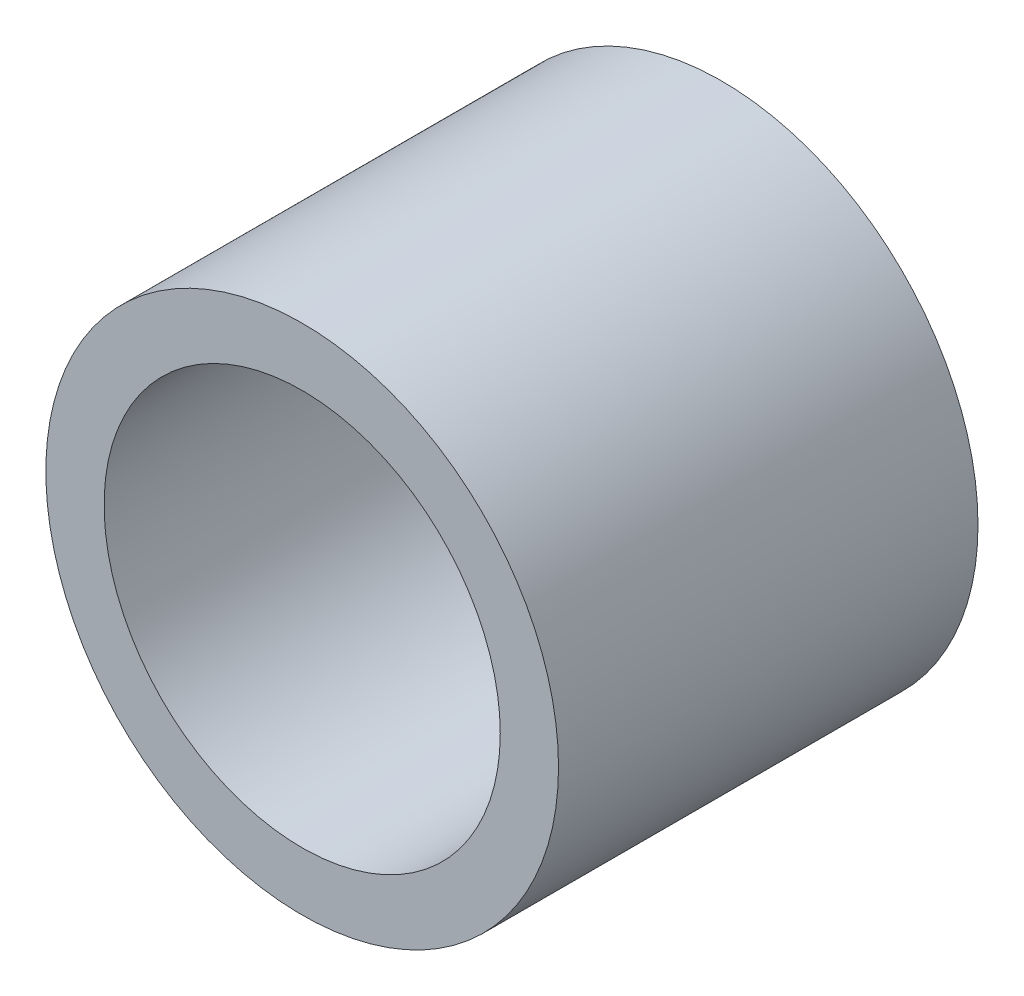
SolidWorks part; units mm, degrees
ref_plane "Alzado" through (0, 0, 0) normal (0, 0, 1) x (1, 0, 0)
ref_plane "Planta" through (0, 0, 0) normal (0, 1, 0) x (1, 0, 0)
ref_plane "Vista lateral" through (0, 0, 0) normal (1, 0, 0) x (0, 0, -1)
sketch "Croquis1" plane through (0, 0, 0) normal (0, 0, 1) x (1, 0, 0)
  circle A0 centre (0, 0) radius 4.25
  circle A1 centre (0, 0) radius 5.5
  dimension "D1" = 8.5
  dimension "D2" = 11
extrude "Saliente-Extruir1" add sketch "Croquis1" along normal blind 9
